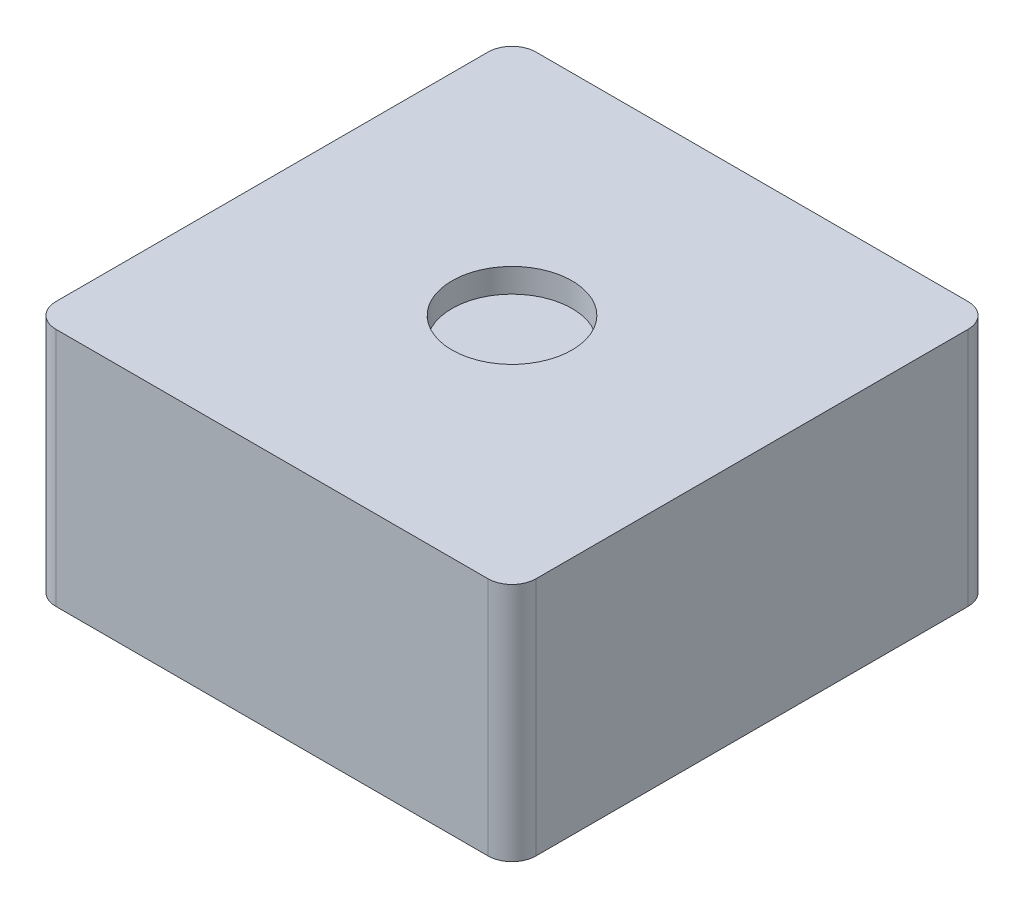
SolidWorks part; units mm, degrees
ref_plane "Front" through (0, 0, 0) normal (0, 0, 1) x (1, 0, 0)
ref_plane "Top" through (0, 0, 0) normal (0, 1, 0) x (1, 0, 0)
ref_plane "Right" through (0, 0, 0) normal (1, 0, 0) x (0, 0, -1)
sketch "草图1" plane through (0, 0, 0) normal (0, 1, 0) x (1, 0, 0)
  line L1 (-1.5238, 2.0476) -> (2.4762, 2.0476)
  line L2 (-1.5238, 2.0476) -> (-1.5238, -1.9524)
  line L3 (-1.5238, -1.9524) -> (2.4762, -1.9524)
  line L4 (2.4762, 2.0476) -> (2.4762, -1.9524)
  dimension "D1" = 4
  dimension "D2" = 4
extrude "凸台-拉伸1" add sketch "草图1" along normal blind 2
sketch "草图2" plane through (0, 2, 0) normal (0, 1, 0) x (1, 0, 0)
  line L0 (2.4762, -1.9524) -> (2.4762, 2.0476) construction
  line L1 (2.4762, 2.0476) -> (-1.5238, 2.0476) construction
  circle A0 centre (0.4762, 0.0476) radius 0.5
  dimension "D1" = 2
  dimension "D2" = 2
extrude "切除-拉伸1" cut sketch "草图2" against normal blind 0.2
fillet "圆角1" radius 0.2 4 edges at (-1.5238, 1, -2.0476) (-1.5238, 1, 1.9524) (2.4762, 1, -2.0476) (2.4762, 1, 1.9524)
